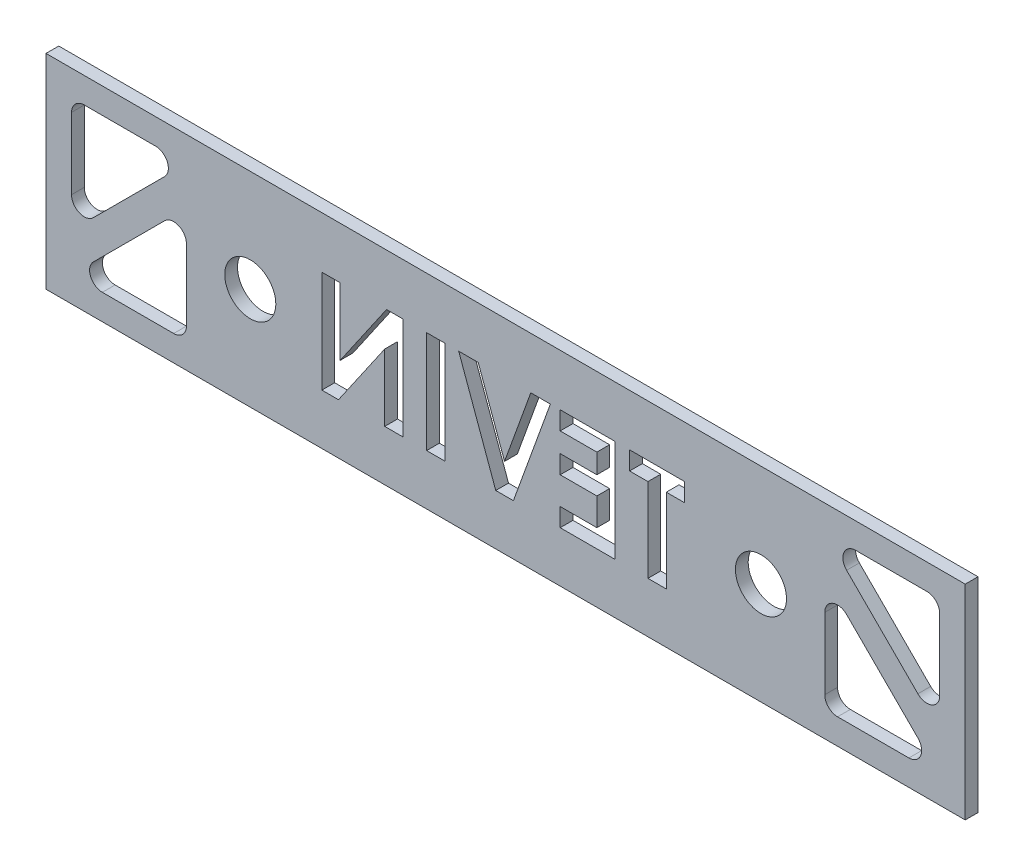
SolidWorks part; units mm, degrees
material "1060 Alloy"
ref_plane "Front Plane" through (0, 0, 0) normal (0, 0, 1) x (1, 0, 0)
ref_plane "Top Plane" through (0, 0, 0) normal (0, 1, 0) x (1, 0, 0)
ref_plane "Right Plane" through (0, 0, 0) normal (1, 0, 0) x (0, 0, -1)
sketch "Sketch1" plane through (0, 0, 0) normal (1, 0, 0) x (0, 0, -1)
  line L1 (5.0884, 8.6191) -> (-1.2616, 8.6191)
  line L2 (5.0884, 8.6191) -> (5.0884, -92.9809)
  line L3 (5.0884, -92.9809) -> (-1.2616, -92.9809)
  line L4 (-1.2616, 8.6191) -> (-1.2616, -92.9809)
  dimension "D1" = 6.35
  dimension "D2" = 101.6
extrude "Boss-Extrude1" add sketch "Sketch1" along normal blind 457.2
sketch "Sketch2" plane through (0, 0, -5.0884) normal (0, 0, -1) x (-1, 0, 0)
  line L0 (-457.2, 8.6191) -> (0, 8.6191) construction
  line L1 (0, -92.9809) -> (0, 8.6191) construction
  line L2 (-457.2, -92.9809) -> (-457.2, 8.6191) construction
  circle A0 centre (-355.6, -42.1809) radius 12.7
  circle A1 centre (-101.6, -42.1809) radius 12.7
  dimension "D1" = 25.4
  dimension "D2" = 25.4
  dimension "D3" = 50.8
  dimension "D4" = 50.8
  dimension "D5" = 101.6
  dimension "D6" = 101.6
extrude "Cut-Extrude1" cut sketch "Sketch2" against normal through all
sketch "Sketch3" plane through (0, 0, -5.0884) normal (0, 0, -1) x (-1, 0, 0)
  line L0 (-438.15, -4.0809) -> (-402.6803, -4.0809)
  line L1 (-444.5, -10.4309) -> (-444.5, -45.9006)
  line L2 (-433.6599, -50.3907) -> (-398.1901, -14.921)
  line L3 (-398.1901, -33.971) -> (-433.6599, -69.4407)
  line L4 (-429.1697, -80.2809) -> (-393.7, -80.2809)
  line L5 (-387.35, -73.9309) -> (-387.35, -38.4611)
  line L6 (-457.2, 8.6191) -> (0, 8.6191) construction
  line L7 (-457.2, -92.9809) -> (-457.2, 8.6191) construction
  line L8 (-457.2, -92.9809) -> (0, -92.9809) construction
  line L9 (-228.6, 8.6191) -> (-228.6, -92.9809) construction
  line L10 (-69.85, -73.9309) -> (-69.85, -38.4611)
  line L11 (-28.0303, -80.2809) -> (-63.5, -80.2809)
  line L12 (-59.0099, -33.971) -> (-23.5401, -69.4407)
  line L13 (-23.5401, -50.3907) -> (-59.0099, -14.921)
  line L14 (-12.7, -10.4309) -> (-12.7, -45.9006)
  line L15 (-19.05, -4.0809) -> (-54.5197, -4.0809)
  arc A0 (-398.1901, -33.971) -> (-387.35, -38.4611) centre (-393.7, -38.4611) cw
  arc A1 (-393.7, -80.2809) -> (-387.35, -73.9309) centre (-393.7, -73.9309) ccw
  arc A2 (-433.6599, -69.4407) -> (-429.1697, -80.2809) centre (-429.1697, -73.9309) ccw
  arc A3 (-444.5, -45.9006) -> (-433.6599, -50.3907) centre (-438.15, -45.9006) ccw
  arc A4 (-402.6803, -4.0809) -> (-398.1901, -14.921) centre (-402.6803, -10.4309) cw
  arc A5 (-438.15, -4.0809) -> (-444.5, -10.4309) centre (-438.15, -10.4309) ccw
  arc A6 (-19.05, -4.0809) -> (-12.7, -10.4309) centre (-19.05, -10.4309) cw
  arc A7 (-54.5197, -4.0809) -> (-59.0099, -14.921) centre (-54.5197, -10.4309) ccw
  arc A8 (-12.7, -45.9006) -> (-23.5401, -50.3907) centre (-19.05, -45.9006) cw
  arc A9 (-23.5401, -69.4407) -> (-28.0303, -80.2809) centre (-28.0303, -73.9309) cw
  arc A10 (-63.5, -80.2809) -> (-69.85, -73.9309) centre (-63.5, -73.9309) cw
  arc A11 (-59.0099, -33.971) -> (-69.85, -38.4611) centre (-63.5, -38.4611) ccw
  text T0 "TEVIN" font "Century Gothic" height 50.8
  point P17 (-387.35, -80.2809)
  point P20 (-444.5, -80.2809)
  point P23 (-444.5, -61.2309)
  point P26 (-387.35, -4.0809)
  point P29 (-444.5, -4.0809)
  point P50 (-12.7, -4.0809)
  point P51 (-69.85, -4.0809)
  point P52 (-12.7, -61.2309)
  point P53 (-12.7, -80.2809)
  point P54 (-69.85, -80.2809)
  dimension "D8" = 6.35
  dimension "D1" = 12.7
  dimension "D2" = 12.7
  dimension "D3" = 12.7
  dimension "D4" = 12.7
  dimension "D5" = 57.15
  dimension "D6" = 57.15
  dimension "D7" = 57.15
extrude "Cut-Extrude2" cut sketch "Sketch3" against normal through all
